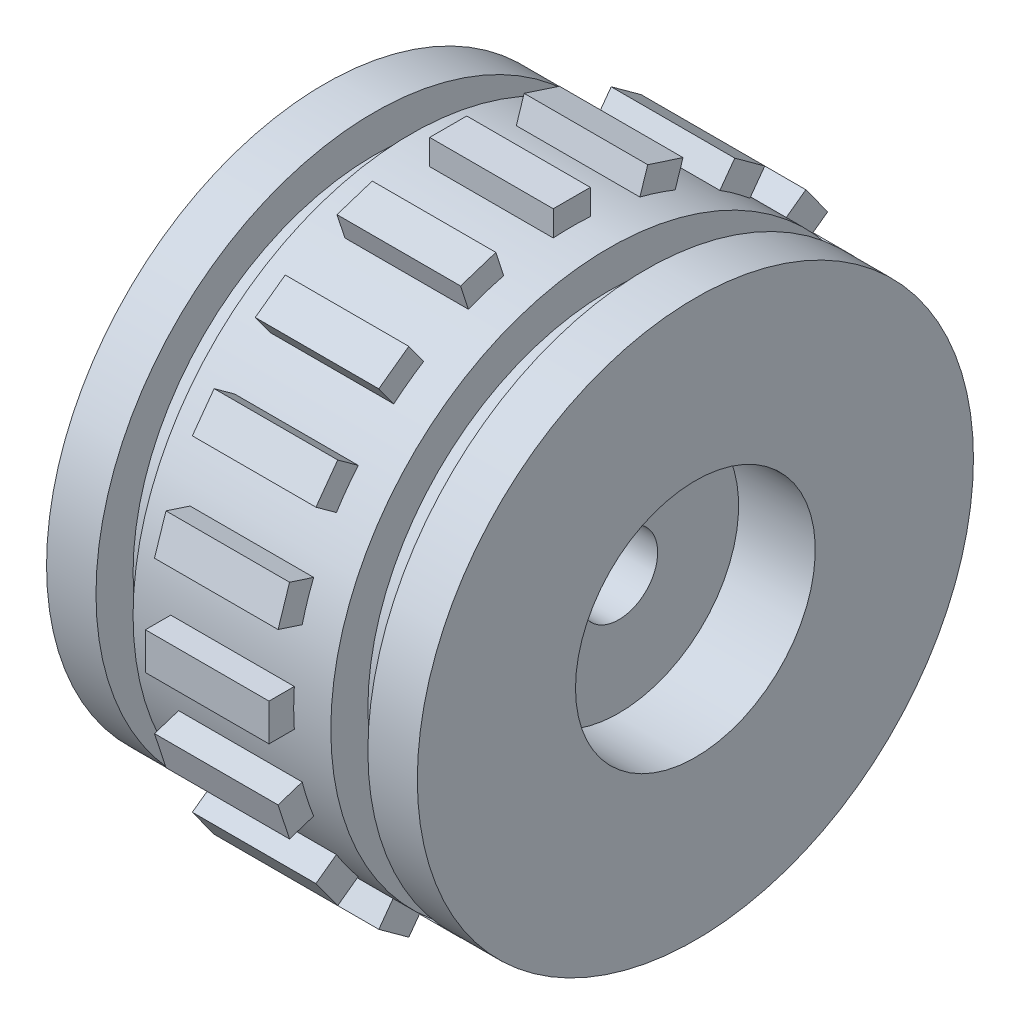
SolidWorks part; units mm, degrees
material "ABS"
ref_plane "Спереди" through (0, 0, 0) normal (0, 0, 1) x (1, 0, 0)
ref_plane "Сверху" through (0, 0, 0) normal (0, 1, 0) x (1, 0, 0)
ref_plane "Справа" through (0, 0, 0) normal (1, 0, 0) x (0, 0, -1)
sketch "Эскиз4" plane through (0, 0, 0) normal (0, 0, 1) x (1, 0, 0)
  line L0 (-30, 0) -> (0, 0) construction
  line L1 (-30, 22.5) -> (-30, 18.5)
  line L2 (-30, 18.5) -> (-19, 18.5)
  line L4 (-19, 18.5) -> (-19, 5.1)
  line L5 (-13, 3.15) -> (0, 3.15)
  line L9 (0, 22.5) -> (-30, 22.5)
  line L11 (-6.2, 3.15) -> (-6.2, 9.7)
  line L15 (0, 22.5) -> (0, 3.15)
  line L17 (-19, 5.1) -> (-13, 5.1)
  line L18 (-13, 5.1) -> (-13, 3.15)
  line L19 (-6.2, 9.7) -> (0, 9.7)
  dimension "D2" = 6
  dimension "D3" = 6.3
  dimension "D4" = 6.2
  dimension "D5" = 45
  dimension "D6" = 10.2
  dimension "D7" = 19.4
  dimension "D8" = 4
  dimension "D9" = 30
  dimension "D12" = 11
revolve "Повернуть1" add sketch "Эскиз4" angle 360 about L0
chamfer "Фаска2" distance 2 angle 45 2 edges at (-30, 0, 18.5) (-19, 0, 18.5)
sketch "Эскиз6" plane through (0, 0, 0) normal (0, 0, 1) x (1, 0, 0)
  line L0 (-30, 18.5) -> (-30, 23.5)
  line L1 (-30, 22.5) -> (-30, -22.5) construction
  line L2 (-30, 23.5) -> (-26, 23.5)
  line L3 (-26, 23.5) -> (-26, 19.5)
  line L4 (-26, 19.5) -> (-23, 19.5)
  line L5 (-23, 19.5) -> (-23, 23.5)
  line L6 (-23, 23.5) -> (-7, 23.5)
  line L7 (-7, 23.5) -> (-7, 19.5)
  line L8 (-7, 19.5) -> (-4, 19.5)
  line L9 (-4, 19.5) -> (-4, 23.5)
  line L10 (-4, 23.5) -> (0, 23.5)
  line L11 (0, 23.5) -> (0, 18.5)
  line L12 (0, -22.5) -> (0, 22.5) construction
  line L13 (0, 18.5) -> (-30, 18.5)
  line L14 (0, 22.5) -> (-30, 22.5) construction
  line L15 (-15, 25.3568) -> (-15, 13.0667) construction
  line L16 (-26, 23.5) -> (-23, 23.5)
  line L17 (-7, 23.5) -> (-4, 23.5)
  dimension "D1" = 4
  dimension "D2" = 5
  dimension "D3" = 1
  dimension "D4" = 4
  dimension "D5" = 3
revolve "Вырез-Повернуть2" cut sketch "Эскиз6" angle 360 about L0
sketch "Эскиз7" plane through (0, 0, 0) normal (0, 0, 1) x (1, 0, 0)
  line L0 (-15, 26.6765) -> (-15, 11.8247) construction
  line L1 (-20, 24.5) -> (-10, 24.5)
  line L2 (-20, 24.5) -> (-20, 21.0633)
  line L3 (-20, 21.0633) -> (-10, 21.0633)
  line L4 (-10, 24.5) -> (-10, 21.0633)
  line L5 (-30, 22.5) -> (-30, -22.5) construction
  line L6 (0, -22.5) -> (0, 22.5) construction
  line L7 (-7, 22.5) -> (-23, 22.5) construction
  dimension "D1" = 10
  dimension "D2" = 2
extrude "Бобышка-Вытянуть1" add sketch "Эскиз7" along normal mid plane 3
pattern_circular "Круговой массив1" count 20 over 360 about axis through (0, 0, 0) along (1, 0, 0) of "Бобышка-Вытянуть1"
